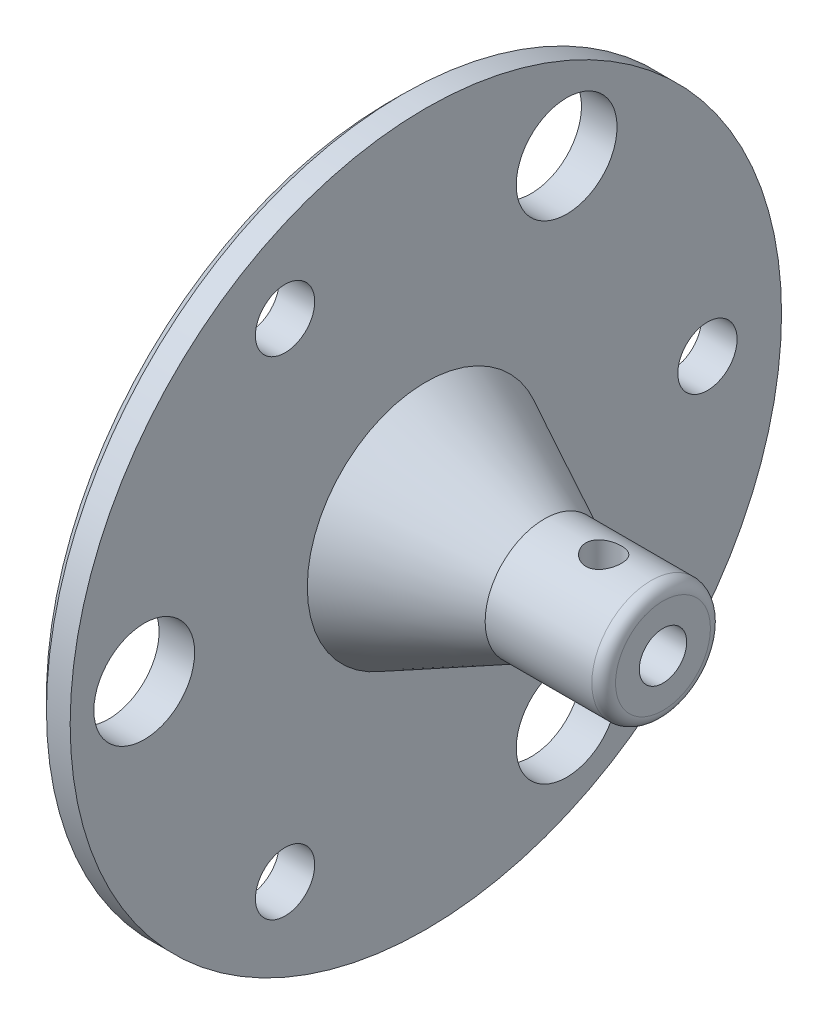
SolidWorks part; units mm, degrees
material "1060 Alloy"
ref_plane "Front Plane" through (0, 0, 0) normal (0, 0, 1) x (1, 0, 0)
ref_plane "Top Plane" through (0, 0, 0) normal (0, 1, 0) x (1, 0, 0)
ref_plane "Right Plane" through (0, 0, 0) normal (1, 0, 0) x (0, 0, -1)
sketch "Sketch1" plane through (0, 0, 0) normal (1, 0, 0) x (0, 0, -1)
  circle A0 centre (0, 0) radius 30
  dimension "D1" = 60
extrude "Boss-Extrude1" add sketch "Sketch1" against normal blind 3
sketch "Sketch2" plane through (0, 0, 0) normal (1, 0, 0) x (0, 0, -1)
  circle A0 centre (0, 0) radius 10
  dimension "D1" = 20
extrude "Boss-Extrude2" add sketch "Sketch2" along normal blind 10
sketch "Sketch3" plane through (10, 0, 0) normal (1, 0, 0) x (0, 0, -1)
  circle A0 centre (0, 0) radius 5
  dimension "D1" = 10
extrude "Boss-Extrude3" add sketch "Sketch3" along normal blind 10
sketch "Sketch4" plane through (0, 0, 0) normal (0, 0, 1) x (1, 0, 0)
  line L0 (10, 5) -> (0, 10)
  line L1 (0, 10) -> (10, 10)
  line L2 (10, 10) -> (10, 5)
  line L3 (0, 0) -> (24.7994, 0) construction
revolve "Cut-Revolve1" cut sketch "Sketch4" angle 360 about L3
sketch "Sketch6" plane through (20, 0, 0) normal (1, 0, 0) x (0, 0, -1)
  circle A0 centre (0, 0) radius 2
  dimension "D1" = 4
extrude "Cut-Extrude1" cut sketch "Sketch6" against normal through all
sketch "Sketch7" plane through (-3, 0, 0) normal (-1, 0, 0) x (0, 0, 1)
  line L1 (23.75, 0) -> (11.875, 20.5681) construction
  line L2 (11.875, 20.5681) -> (-11.875, 20.5681) construction
  line L3 (-11.875, 20.5681) -> (-23.75, 0) construction
  line L4 (-23.75, 0) -> (-11.875, -20.5681) construction
  line L5 (-11.875, -20.5681) -> (11.875, -20.5681) construction
  line L6 (11.875, -20.5681) -> (23.75, 0) construction
  circle A0 centre (0, 0) radius 23.75 construction
  circle A1 centre (-11.875, 20.5681) radius 4.25
  circle A2 centre (23.75, 0) radius 4.25
  circle A3 centre (-11.875, -20.5681) radius 4.25
  circle A4 centre (11.875, 20.5681) radius 2.5
  circle A5 centre (11.875, -20.5681) radius 2.5
  circle A6 centre (-23.75, 0) radius 2.5
  point P16 (0, 0)
  point P22 (0, 0)
  dimension "D1" = 47.5
  dimension "D2" = 8.5
  dimension "D4" = 5
  dimension "D3" = 3
  dimension "D5" = 3
extrude "Cut-Extrude2" cut sketch "Sketch7" against normal up to next
sketch "Sketch8" plane through (0, 0, 0) normal (0, 1, 0) x (1, 0, 0)
  line L0 (0, 0) -> (20, 0) construction
  line L1 (20, -5) -> (20, 5) construction
  circle A0 centre (15, 0) radius 1.5
  dimension "D1" = 3
  dimension "D2" = 5
extrude "Cut-Extrude3" cut sketch "Sketch8" along normal blind 15 contours A0
fillet "Fillet1" radius 1 1 edges at (20, 0, -5)
chamfer "Chamfer1" distance 1 1 edges at (-3, 0, -30)
chamfer "Chamfer2" distance 1 1 edges at (-3, 0, -2)
